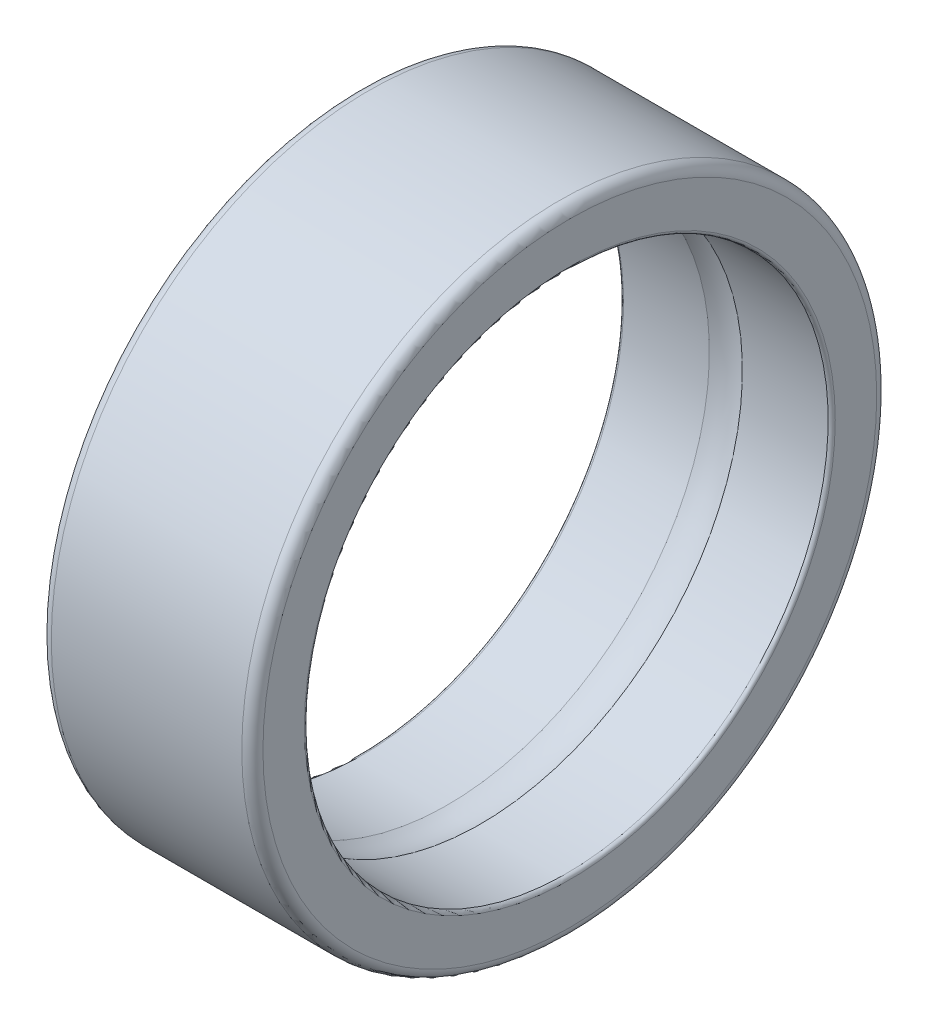
SolidWorks part; units mm, degrees
ref_plane "Front Plane" through (0, 0, 0) normal (0, 0, 1) x (1, 0, 0)
ref_plane "Top Plane" through (0, 0, 0) normal (0, 1, 0) x (1, 0, 0)
ref_plane "Right Plane" through (0, 0, 0) normal (1, 0, 0) x (0, 0, -1)
ref_plane "Plane1"
sketch "Sketch1" plane through (0, 0, 0) normal (0, 0, 1) x (1, 0, 0)
  line L0 (0.0667, 4.95) -> (1.6878, 4.95)
  line L1 (2.3122, 4.95) -> (3.9333, 4.95)
  line L2 (4, 5.0167) -> (4, 5.8)
  line L3 (3.8, 6) -> (0.2, 6)
  line L4 (0, 5.8) -> (0, 5.0167)
  line L5 (4, 0) -> (-4, 0) construction
  arc A0 (0, 5.0167) -> (0.0667, 4.95) centre (0.0667, 5.0167) ccw
  arc A1 (2.3122, 4.95) -> (1.6878, 4.95) centre (2, 4) ccw
  arc A2 (3.9333, 4.95) -> (4, 5.0167) centre (3.9333, 5.0167) ccw
  arc A3 (4, 5.8) -> (3.8, 6) centre (3.8, 5.8) ccw
  arc A4 (0.2, 6) -> (0, 5.8) centre (0.2, 5.8) ccw
revolve "Revolução1" add sketch "Sketch1" angle 360 about L5
